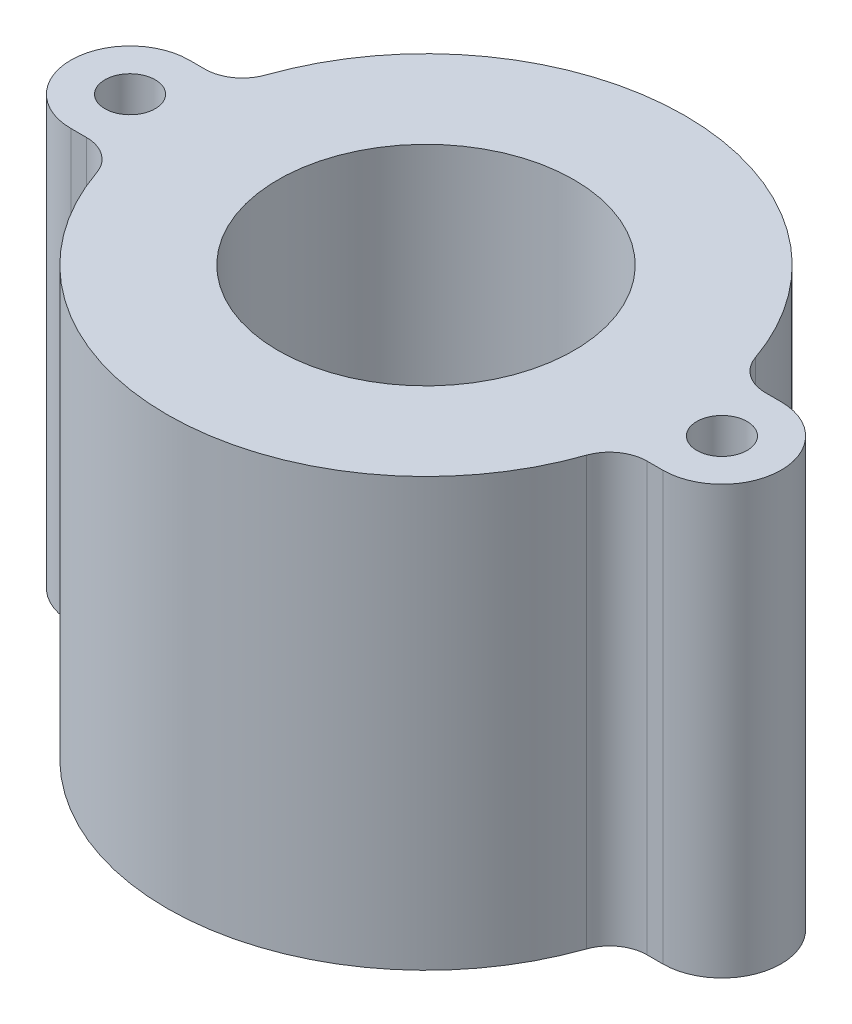
SolidWorks part; units mm, degrees
ref_plane "Front Plane" through (0, 0, 0) normal (0, 0, 1) x (1, 0, 0)
ref_plane "Top Plane" through (0, 0, 0) normal (0, 1, 0) x (1, 0, 0)
ref_plane "Right Plane" through (0, 0, 0) normal (1, 0, 0) x (0, 0, -1)
sketch "Sketch1" plane through (0, 0, 0) normal (0, 1, 0) x (1, 0, 0)
  line L1 (20, -4) -> (-20, -4)
  line L2 (20, -4) -> (20, 4)
  line L3 (20, 4) -> (-20, 4)
  line L4 (-20, -4) -> (-20, 4)
  line L5 (20, -4) -> (-20, 4) construction
  line L6 (20, 4) -> (-20, -4) construction
  circle A0 centre (0, 0) radius 17.5
  arc A1 (-20, 4) -> (-20, -4) centre (-20, 0) ccw
  arc A2 (20, 4) -> (20, -4) centre (20, 0) cw
  circle A3 centre (0, 0) radius 10
  point P12 (-20, 0)
  point P13 (20, 0)
  dimension "D2" = 35
  dimension "D4" = 20
  dimension "D1" = 40
  dimension "D3" = 8
extrude "Boss-Extrude1" add sketch "Sketch1" along normal blind 28.9 contours A3 L3 A0 | A3 L3 A0 L1 | A3 L1 A0 | A3 L1 A0 L3 | A0 L1 L2 L3 | A2 L2 | L4 A1 | A0 L3 L4 L1
fillet "Fillet1" radius 2.54 4 edges at (-17.0367, 14.45, -4) (17.0367, 14.45, -4) (-17.0367, 14.45, 4) (17.0367, 14.45, 4)
hole_wizard "M3 Clearance Hole1" positions "Sketch2" profile "Sketch3" hole size "M3" standard "ANSI Metric" end condition through all
sketch "Sketch2" plane through (0, 28.9, 0) normal (0, 1, 0) x (1, 0, 0)
  point P0 (-20, 0)
  point P3 (20, 0)
sketch "Sketch3" plane through (-20, 28.9, 0) normal (1, 0, 0) x (0, 0, 1)
  line L0 (0, 0) -> (0, 28.9)
  line L1 (0, 28.9) -> (1.7, 28.9)
  line L2 (1.7, 28.9) -> (1.7, 0)
  line L5 (1.7, 0) -> (0, 0)
  line L11 (0, -6.35) -> (0, 107.95) construction
  dimension "Thru Hole Dia." = 3.4
  dimension "Thru Hole Depth" = 28.9
